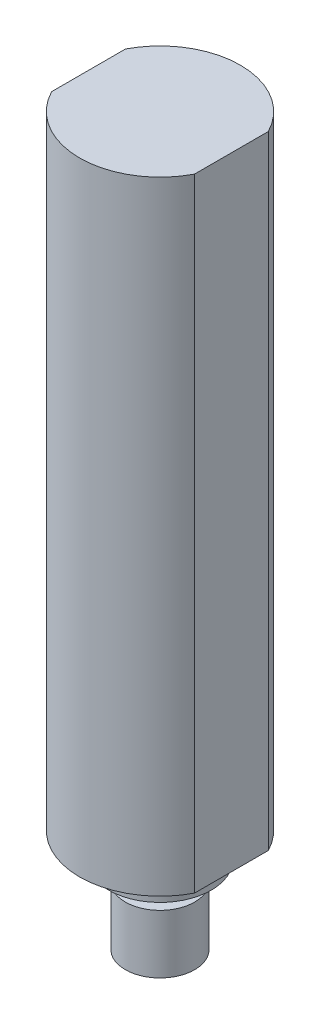
SolidWorks part; units mm, degrees
ref_plane "Front Plane" through (0, 0, 0) normal (0, 0, 1) x (1, 0, 0)
ref_plane "Top Plane" through (0, 0, 0) normal (0, 1, 0) x (1, 0, 0)
ref_plane "Right Plane" through (0, 0, 0) normal (1, 0, 0) x (0, 0, -1)
sketch "Sketch1" plane through (0, 0, 0) normal (0, 0, 1) x (1, 0, 0)
  line L0 (0, 72.4546) -> (0, -72.6875) construction
  line L1 (0, 0) -> (4.74, 0)
  line L2 (4.74, 0) -> (4.74, 8)
  line L3 (4.74, 8) -> (1, 8)
  line L4 (1, 8) -> (1, 10.53)
  line L5 (1, 10.53) -> (7, 10.53)
  line L6 (7, 10.53) -> (7, 14.08)
  line L7 (7, 14.08) -> (10.975, 14.08)
  line L8 (10.975, 14.08) -> (10.975, 99.08)
  line L9 (10.975, 99.08) -> (0, 99.08)
  line L10 (0, 99.08) -> (0, 0)
  point P5 (10.975, 56.58)
  dimension "D1" = 4.74
  dimension "D2" = 10.975
  dimension "D3" = 42.5
  dimension "D4" = 8
  dimension "D5" = 3.55
  dimension "D6" = 2.53
  dimension "D7" = 7
  dimension "D8" = 1
revolve "Revolve1" add sketch "Sketch1" angle 360 about L0
sketch "Sketch2" plane through (0, 99.08, 0) normal (0, 1, 0) x (1, 0, 0)
  line L0 (-9.75, 5.0387) -> (-9.75, -5.0387)
  line L1 (9.75, -5.0387) -> (9.75, 5.0387)
  line L2 (-9.75, 5.0387) -> (9.75, 5.0387) construction
  circle A0 centre (0, 0) radius 10.975 construction
  arc A1 (-9.75, 5.0387) -> (-9.75, -5.0387) centre (0, 0) ccw
  arc A2 (9.75, -5.0387) -> (9.75, 5.0387) centre (0, 0) ccw
  dimension "D1" = 19.5
extrude "Cut-Extrude1" cut sketch "Sketch2" against normal through all
